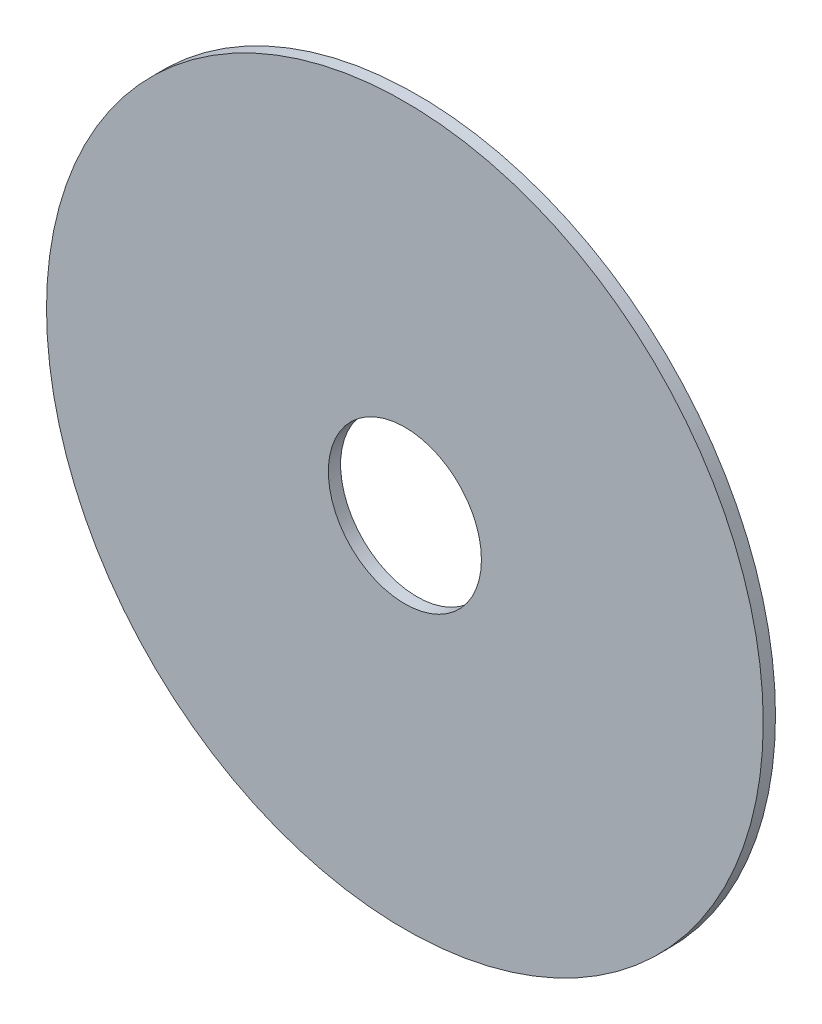
SolidWorks part; units mm, degrees
ref_plane "Front Plane" through (0, 0, 0) normal (0, 0, 1) x (1, 0, 0)
ref_plane "Top Plane" through (0, 0, 0) normal (0, 1, 0) x (1, 0, 0)
ref_plane "Right Plane" through (0, 0, 0) normal (1, 0, 0) x (0, 0, -1)
sketch "Sketch1" plane through (0, 0, 0) normal (0, 0, 1) x (1, 0, 0)
  circle A0 centre (0, 0) radius 66.8909
  circle A1 centre (0, 0) radius 14.2875
  dimension "D1" = 133.7818
  dimension "D2" = 28.575
extrude "Boss-Extrude1" add sketch "Sketch1" along normal blind 2.286
